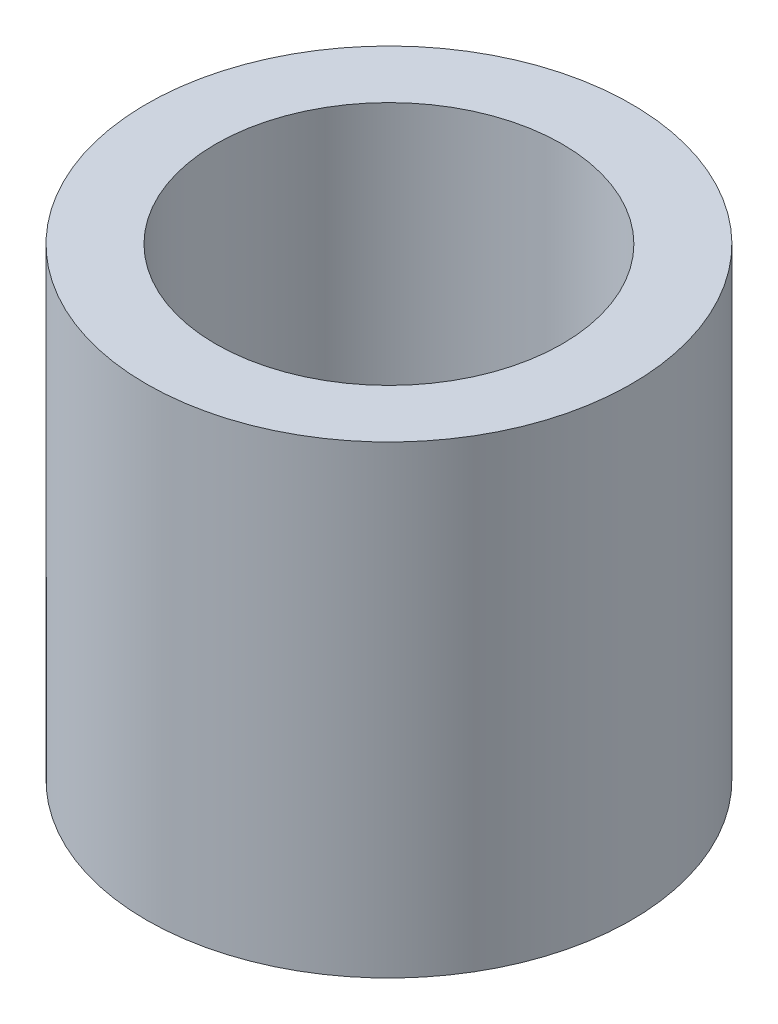
SolidWorks part; units mm, degrees
ref_plane "Front Plane" through (0, 0, 0) normal (0, 0, 1) x (1, 0, 0)
ref_plane "Top Plane" through (0, 0, 0) normal (0, 1, 0) x (1, 0, 0)
ref_plane "Right Plane" through (0, 0, 0) normal (1, 0, 0) x (0, 0, -1)
sketch "Sketch1" plane through (0, 0, 0) normal (0, 1, 0) x (1, 0, 0)
  circle A0 centre (0, 0) radius 2.5
  circle A1 centre (0, 0) radius 3.5
  dimension "D1" = 5
  dimension "D2" = 7
extrude "Boss-Extrude1" add sketch "Sketch1" along normal blind 6.7 contours A1
